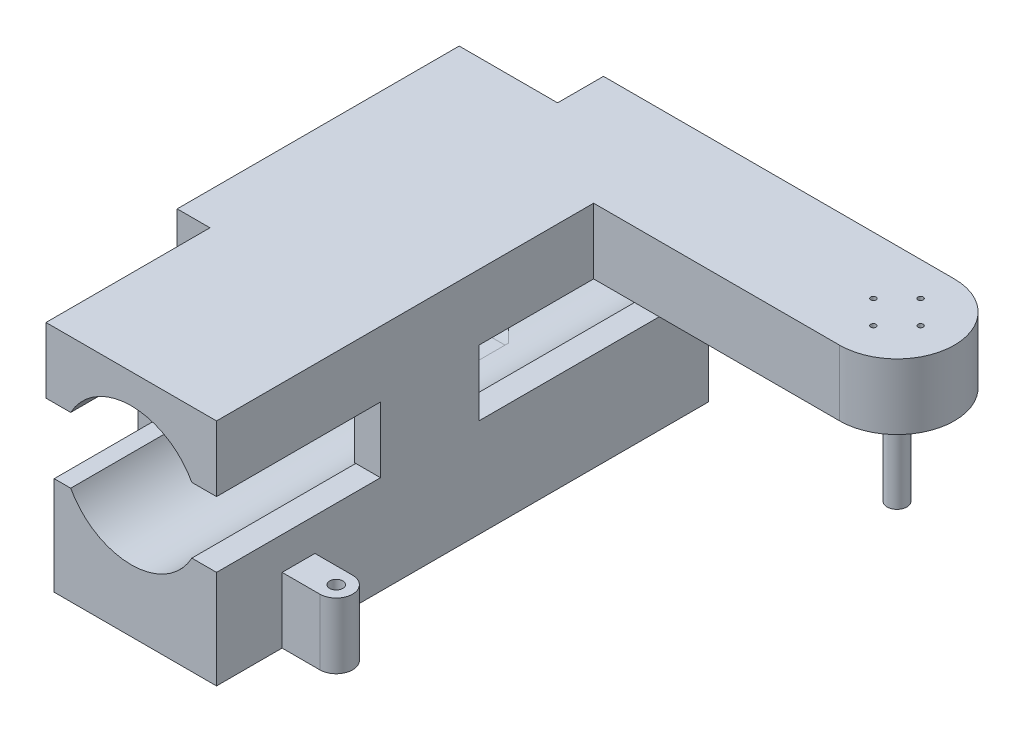
SolidWorks part; units mm, degrees
ref_plane "正面" through (0, 0, 0) normal (0, 0, 1) x (1, 0, 0)
ref_plane "平面" through (0, 0, 0) normal (0, 1, 0) x (1, 0, 0)
ref_plane "右側面" through (0, 0, 0) normal (1, 0, 0) x (0, 0, -1)
sketch "ｽｹｯﾁ2" plane through (0, 0, 0) normal (0, 0, 1) x (1, 0, 0)
  line L0 (-26, 0) -> (-26, -40)
  line L1 (-26, -40) -> (26, -40)
  line L2 (26, -40) -> (26, 0)
  line L3 (-26, 0) -> (-26, 30)
  line L4 (-26, 30) -> (26, 30)
  line L5 (26, 30) -> (26, 0)
  circle A0 centre (0, 0) radius 21
  circle A1 centre (0, 0) radius 26
  dimension "D1" = 42
  dimension "D2" = 52
  dimension "D3" = 40
  dimension "D4" = 30
extrude "ﾎﾞｽ - 押し出し1" add sketch "ｽｹｯﾁ2" along normal blind 140 and the other way blind 10 contours A1 L0 L1 L2 | A0
ref_plane "平面1" through (0, 0, 140) normal (0, 0, 1) x (1, 0, 0)
sketch "ｽｹｯﾁ3" plane through (0, 0, 140) normal (0, 0, 1) x (1, 0, 0)
  line L1 (-47.1336, 10) -> (47.1336, 10)
  line L2 (-47.1336, 10) -> (-47.1336, -10)
  line L3 (-47.1336, -10) -> (47.1336, -10)
  line L4 (47.1336, 10) -> (47.1336, -10)
  line L5 (-47.1336, 10) -> (47.1336, -10) construction
  line L6 (-47.1336, -10) -> (47.1336, 10) construction
  point P0 (0, 0)
  dimension "D1" = 20
extrude "ｶｯﾄ - 押し出し1" cut sketch "ｽｹｯﾁ3" against normal blind 50
sketch "ｽｹｯﾁ4" plane through (0, 0, 140) normal (0, 0, 1) x (1, 0, 0)
  line L0 (-26, -10) -> (-26, -40)
  line L1 (-26, -40) -> (-23.5, -40)
  line L2 (-26, -40) -> (26, -40) construction
  line L3 (-23.5, -40) -> (-23.5, -10)
  line L4 (-26, -10) -> (26, -10) construction
  line L5 (-23.5, -10) -> (-26, -10)
  dimension "D1" = 23.5
extrude "ｶｯﾄ - 押し出し2" cut sketch "ｽｹｯﾁ4" against normal blind 38
ref_plane "平面2" through (0, -40, 0) normal (0, -1, 0) x (-1, 0, 0)
sketch "ｽｹｯﾁ6" plane through (0, -40, 0) normal (0, -1, 0) x (-1, 0, 0)
  line L0 (-26, -120) -> (-37.5, -120)
  line L1 (-26, -140) -> (-26, 10) construction
  line L2 (-37.5, -120) -> (-37.5, -110)
  line L3 (-37.5, -110) -> (-26, -110)
  line L4 (-26, -110) -> (-26, -120)
  line L5 (23.5, -140) -> (-26, -140) construction
  circle A0 centre (-37.5, -115) radius 5
  circle A1 centre (-37.5, -115) radius 2
  point P12 (-1.25, -140)
  dimension "D3" = 4
  dimension "D1" = 37.5
  dimension "D2" = 10
  dimension "D4" = 20
  dimension "D5" = 36.25
extrude "ﾎﾞｽ - 押し出し2" add sketch "ｽｹｯﾁ6" against normal blind 20 contours A0 L0 L4 L3 | A1 L2 A0 | A1 L2 A0
sketch "ｽｹｯﾁ8" plane through (0, 0, 0) normal (0, 1, 0) x (1, 0, 0)
  circle A0 centre (0, -25) radius 21
  dimension "D1" = 42
  dimension "D2" = 25
sketch "ｽｹｯﾁ9" plane through (0, -40, 0) normal (0, -1, 0) x (-1, 0, 0)
  line L0 (-55, -140) -> (55, -140) construction
  line L1 (7.5, 60) -> (-7.5, 60)
  line L2 (7.5, 60) -> (7.5, -60)
  line L3 (7.5, -60) -> (-7.5, -60)
  line L4 (-7.5, 60) -> (-7.5, -60)
  line L5 (7.5, 60) -> (-7.5, -60) construction
  line L6 (7.5, -60) -> (-7.5, 60) construction
  point P0 (0, 0)
  dimension "D1" = 15
  dimension "D2" = 80
ref_plane "平面3" through (0, 0, -10) normal (0, 0, -1) x (-1, 0, 0)
sketch "ｽｹｯﾁ12" plane through (0, 0, 0) normal (0, 0, 1) x (1, 0, 0)
  circle A0 centre (0, 0) radius 21
extrude "ｶｯﾄ - 押し出し7" cut sketch "ｽｹｯﾁ12" against normal through all both and the other way through all
ref_plane "平面4" through (0, 30, 0) normal (0, 1, 0) x (1, 0, 0)
ref_plane "平面5" through (-26, 0, 0) normal (-1, 0, 0) x (0, 0, 1)
sketch "ｽｹｯﾁ13" plane through (-26, 0, 0) normal (-1, 0, 0) x (0, 0, 1)
  line L0 (46, 0) -> (4, 0) construction
  circle A0 centre (25, 0) radius 21
  dimension "D1" = 42
ref_plane "平面6" through (26, 0, 0) normal (1, 0, 0) x (0, 0, -1)
sketch "ｽｹｯﾁ14" plane through (26, 0, 0) normal (1, 0, 0) x (0, 0, -1)
  line L0 (10, 10) -> (-90, 10)
  line L1 (10, -40) -> (10, 30) construction
  line L2 (-90, 10) -> (-90, -10)
  line L3 (-90, -10) -> (10, -10)
  line L4 (10, -10) -> (10, 10)
  line L5 (-4, 0) -> (-46, 0) construction
  dimension "D1" = 10
  dimension "D2" = 20
  dimension "D3" = 100
extrude "ｶｯﾄ - 押し出し10" cut sketch "ｽｹｯﾁ14" against normal blind 10
sketch "ｽｹｯﾁ15" plane through (0, 0, -10) normal (0, 0, -1) x (-1, 0, 0)
  line L0 (26, 30) -> (26, -40)
  line L1 (34.1, 30) -> (-34.1, 30) construction
  line L2 (26, -11) -> (26, 11) construction
  line L3 (-43.175, -40) -> (43.175, -40) construction
  line L4 (26, 30) -> (26, -40) construction
  line L5 (26, -40) -> (36, -40)
  line L6 (36, -40) -> (36, 30)
  line L7 (36, 30) -> (26, 30)
  dimension "D1" = 10
extrude "ﾎﾞｽ - 押し出し3" add sketch "ｽｹｯﾁ15" against normal blind 100
sketch "ｽｹｯﾁ16" plane through (0, 0, -10) normal (0, 0, -1) x (-1, 0, 0)
  line L0 (36, -40) -> (36, -10)
  line L1 (-37.675, -40) -> (37.675, -40) construction
  line L2 (36, -40) -> (36, 30) construction
  line L3 (36, -10) -> (26, -10)
  line L4 (26, -10) -> (26, -40)
  line L5 (26, -40) -> (36, -40)
  dimension "D1" = 10
  dimension "D2" = 30
extrude "ﾎﾞｽ - 押し出し4" add sketch "ｽｹｯﾁ16" against normal blind 92
ref_plane "平面7" through (-36, 0, 0) normal (-1, 0, 0) x (0, 0, 1)
sketch "ｽｹｯﾁ17" plane through (-36, 0, 0) normal (-1, 0, 0) x (0, 0, 1)
  line L0 (-10, 34.1) -> (-10, -34.1) construction
  circle A0 centre (25, 0) radius 21
  dimension "D1" = 35
extrude "ｶｯﾄ - 押し出し11" cut sketch "ｽｹｯﾁ17" against normal blind 35
sketch "ｽｹｯﾁ18" plane through (0, 0, 0) normal (0, 1, 0) x (1, 0, 0)
  circle A0 centre (0, -66) radius 20
  circle A1 centre (37.5, -115) radius 19
  dimension "D1" = 40
  dimension "D2" = 38
  dimension "D3" = 41
sketch "ｽｹｯﾁ19" plane through (-36, 0, 0) normal (-1, 0, 0) x (0, 0, 1)
  line L0 (4, 0) -> (4, -40)
  line L1 (46, 0) -> (4, 0) construction
  line L2 (60, -40) -> (-60, -40) construction
  line L3 (4, -40) -> (-10, -40)
  line L4 (-60, -40) -> (60, -40) construction
  line L5 (-10, 28.6) -> (-10, -28.6) construction
  line L6 (-10, -40) -> (-10, 30)
  line L7 (28.6, 30) -> (-28.6, 30) construction
  line L8 (-10, 30) -> (5.8272, 30)
  line L9 (4, 0) -> (4, 30)
  circle A0 centre (25, 0) radius 21 construction
sketch "ｽｹｯﾁ20" plane through (-36, 0, 0) normal (-1, 0, 0) x (0, 0, 1)
  line L0 (25, -21) -> (25, 21)
  line L1 (25, 21) -> (-10, 21)
  line L2 (-10, -40) -> (-10, 30) construction
  line L3 (-10, 21) -> (-10, -21)
  line L4 (-10, -21) -> (25, -21)
  line L5 (-10, -21) -> (-10, -40)
  line L6 (-10, -40) -> (4, -40)
  line L7 (4, -40) -> (4, -21)
  line L8 (4, 0) -> (4, -40) construction
  line L9 (4, -21) -> (4, 30)
  line L10 (4, 30) -> (-10, 30)
  line L11 (-10, 30) -> (-10, 21)
  circle A0 centre (25, 0) radius 21 construction
extrude "ｶｯﾄ - 押し出し15" cut sketch "ｽｹｯﾁ20" against normal blind 30 contours L6 L7 L4 L5 | L4 L9 L1 L3 | L10 L11 L1 L9 | L9 L4 L0 L1
sketch "ｽｹｯﾁ21" plane through (0, 30, 0) normal (0, 1, 0) x (1, 0, 0)
  circle A0 centre (0, -106) radius 20
  dimension "D1" = 40
  dimension "D2" = 40
ref_plane "平面8" through (0, 0, 102) normal (0, 0, 1) x (1, 0, 0)
sketch "ｽｹｯﾁ22" plane through (0, 0, 102) normal (0, 0, 1) x (1, 0, 0)
  line L0 (-23.254, -40.0742) -> (-36, -40)
  line L1 (-36, -40) -> (-36, 30) construction
  line L2 (-36, -40) -> (-36, -10)
  line L3 (-36, 0) -> (-36, -40) construction
  line L4 (-36, -10) -> (-26, -10)
  line L5 (-26, -10) -> (-26, -40.0582)
extrude "ﾎﾞｽ - 押し出し5" add sketch "ｽｹｯﾁ22" against normal blind 40 contours L5 L4 L2 L0
sketch "ｽｹｯﾁ23" plane through (-36, 0, 0) normal (-1, 0, 0) x (0, 0, 1)
  line L0 (46, 0) -> (4, 0) construction
  line L1 (46, 21) -> (25, 21)
  line L2 (25, 21) -> (25, -21)
  line L3 (25, -21) -> (46, -21)
  circle A0 centre (46, 0) radius 21
  circle A1 centre (25, 0) radius 21 construction
  dimension "D1" = 42
extrude "ｶｯﾄ - 押し出し16" cut sketch "ｽｹｯﾁ23" against normal blind 35 contours A0 | A0 L1 L2 | A0 L2 L3
sketch "ｽｹｯﾁ24" plane through (26, 0, 0) normal (1, 0, 0) x (0, 0, -1)
  line L0 (-90, -10) -> (-60, -10)
  line L1 (-140, -10) -> (10, -10) construction
  line L2 (-60, -10) -> (-60, 10)
  line L3 (10, 10) -> (-140, 10) construction
  line L4 (-60, 10) -> (-90, 10)
  line L5 (-90, 10) -> (-90, -10)
  line L6 (-140, 55) -> (-140, -55) construction
  dimension "D1" = 30
  dimension "D2" = 50
extrude "ﾎﾞｽ - 押し出し6" add sketch "ｽｹｯﾁ24" against normal blind 8
sketch "ｽｹｯﾁ25" plane through (26, 0, 0) normal (1, 0, 0) x (0, 0, -1)
  line L0 (10, 30) -> (10, 10)
  line L1 (10, 10) -> (-25, 10)
  line L2 (10, 10) -> (-60, 10) construction
  line L3 (-25, 10) -> (-25, 30)
  line L4 (34.1, 30) -> (-34.1, 30) construction
  line L5 (-25, 30) -> (10, 30)
  line L6 (10, 50) -> (-25, 50)
  line L7 (10, -55) -> (10, 55) construction
  line L8 (-25, 50) -> (-25, 30)
  line L9 (10, 30) -> (10, 50)
  dimension "D1" = 20
  dimension "D2" = 35
extrude "ﾎﾞｽ - 押し出し7" add sketch "ｽｹｯﾁ25" along normal blind 75 contours L5 L3 L1 L0
sketch "ｽｹｯﾁ26" plane through (0, 30, 0) normal (0, 1, 0) x (1, 0, 0)
  line L0 (101, 10) -> (101, -25) construction
  circle A0 centre (101, -7.5) radius 17.5
extrude "ﾎﾞｽ - 押し出し8" add sketch "ｽｹｯﾁ26" against normal blind 20
sketch "ｽｹｯﾁ27" plane through (0, 30, 0) normal (0, 1, 0) x (1, 0, 0)
  circle A0 centre (101, -7.5) radius 3
  dimension "D1" = 6
extrude "ﾎﾞｽ - 押し出し9" add sketch "ｽｹｯﾁ27" against normal blind 50
hole_wizard "M2x0.4 ねじ穴1" positions "ｽｹｯﾁ29" profile "ｽｹｯﾁ30" tap size "M2x0.4" standard "JIS" end condition through all
sketch "ｽｹｯﾁ29" plane through (0, 30, 0) normal (0, 1, 0) x (1, 0, 0)
  line L0 (16.5, 10) -> (-16.5, 10) construction
  line L1 (101, -25) -> (26, -25) construction
  point P0 (101, -0.3)
  point P2 (101, -14.7)
  point P4 (108.2, -7.5)
  point P6 (93.8, -7.5)
  dimension "D1" = 0
  dimension "D2" = 0
  dimension "D3" = 17.5
  dimension "D4" = 7.2
  dimension "D5" = 7.2
  dimension "D6" = 7.2
  dimension "D7" = 7.2
  dimension "D8" = 17.5
sketch "ｽｹｯﾁ30" plane through (101, 30, 0.3) normal (1, 0, 0) x (0, 0, 1)
  line L0 (0, 0) -> (0, 70.0582)
  line L1 (0, 70.0582) -> (0.8, 70.0582)
  line L2 (0.8, 70.0582) -> (0.8, 0)
  line L5 (0.8, 0) -> (0, 0)
  line L11 (0, -6.35) -> (0, 107.95) construction
  dimension "次ｻｰﾌｪｽまでのねじ下穴ﾄﾞﾘﾙ直径" = 1.6
  dimension "次ｻｰﾌｪｽまでのねじ下穴ﾄﾞﾘﾙの深さ" = 70.0582
cosmetic thread "穴のねじ山1" parameters "D2"=2
cosmetic thread "穴のねじ山2" parameters "D2"=2
cosmetic thread "穴のねじ山3" parameters "D2"=2
cosmetic thread "穴のねじ山4" parameters "D2"=2
